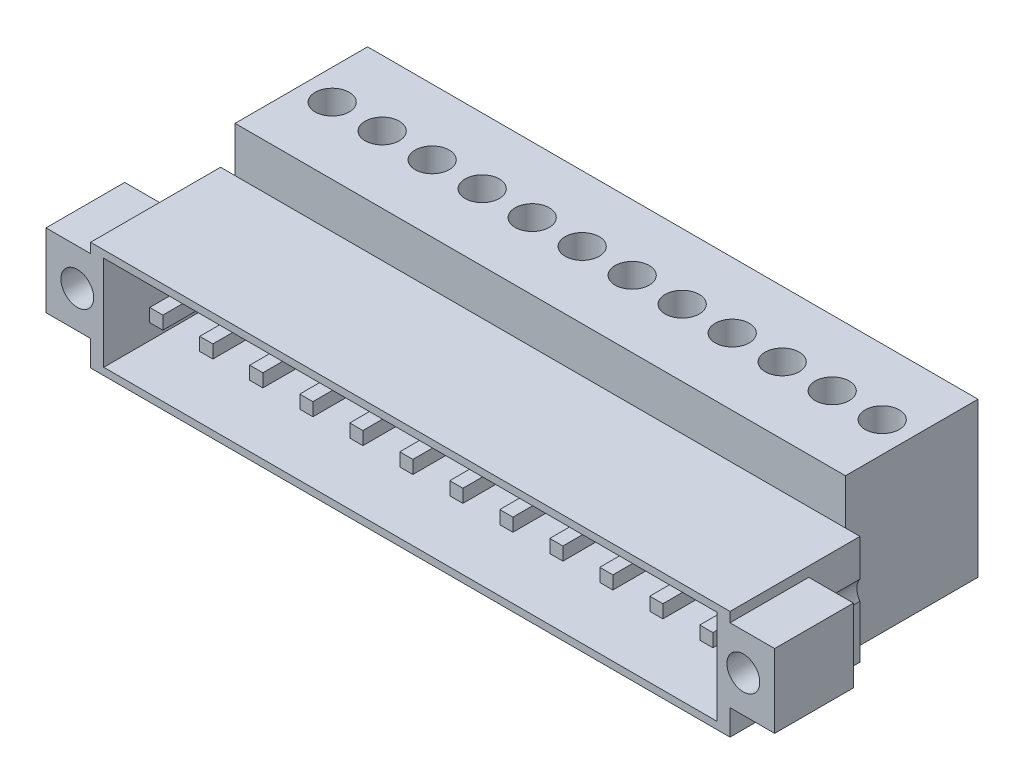
SolidWorks part; units mm, degrees
ref_plane "Front Plane" through (0, 0, 0) normal (0, 0, 1) x (1, 0, 0)
ref_plane "Top Plane" through (0, 0, 0) normal (0, 1, 0) x (1, 0, 0)
ref_plane "Right Plane" through (0, 0, 0) normal (1, 0, 0) x (0, 0, -1)
ref_plane "PL mating face" through (0, 0, 3) normal (0, 0, 1) x (1, 0, 0)
sketch "SK Shroud" plane through (0, 0, 3) normal (0, 0, 1) x (1, 0, 0)
  line L0 (-24.36, -4.75) -> (24.36, -4.75)
  line L1 (24.36, -4.75) -> (24.36, 3.55)
  line L2 (24.36, 3.55) -> (-24.36, 3.55)
  line L3 (-24.36, 3.55) -> (-24.36, -4.75)
extrude "Shroud" add sketch "SK Shroud" against normal blind 9.9
sketch "SK Flange ears" plane through (0, 0, 3) normal (0, 0, 1) x (1, 0, 0)
  line L0 (24.36, -2.8) -> (27.76, -2.8)
  line L1 (27.76, -2.8) -> (27.76, 2.8)
  line L2 (27.76, 2.8) -> (24.36, 2.8)
  line L3 (24.36, 2.8) -> (24.36, -2.8)
  line L4 (-27.76, -2.8) -> (-24.36, -2.8)
  line L5 (-24.36, -2.8) -> (-24.36, 2.8)
  line L6 (-24.36, 2.8) -> (-27.76, 2.8)
  line L7 (-27.76, 2.8) -> (-27.76, -2.8)
extrude "Flange ears" add sketch "SK Flange ears" against normal blind 6
sketch "SK Cavity" plane through (0, 0, 3) normal (0, 0, 1) x (1, 0, 0)
  line L0 (-23.36, -4.2) -> (23.36, -4.2)
  line L1 (23.36, -4.2) -> (23.36, 3)
  line L2 (23.36, 3) -> (-23.36, 3)
  line L3 (-23.36, 3) -> (-23.36, -4.2)
extrude "Cavity" cut sketch "SK Cavity" against normal blind 7.6
ref_plane "PL shroud rear" through (0, 0, -6.9) normal (0, 0, 1) x (1, 0, 0)
sketch "SK Terminal block" plane through (0, 0, -6.9) normal (0, 0, 1) x (1, 0, 0)
  line L0 (-23.255, -4.75) -> (23.255, -4.75)
  line L1 (23.255, -4.75) -> (23.255, 7)
  line L2 (23.255, 7) -> (-23.255, 7)
  line L3 (-23.255, 7) -> (-23.255, -4.75)
extrude "Terminal block" add sketch "SK Terminal block" against normal blind 10.1
sketch "SK Insert holes" plane through (0, 0, 0) normal (0, 0, 1) x (1, 0, 0)
  circle A0 centre (-25.375, 0) radius 1.25
  circle A1 centre (25.375, 0) radius 1.25
extrude "Insert holes" cut sketch "SK Insert holes" against normal through all and the other way through all
ref_plane "PL cavity floor" through (0, 0, -4.6) normal (0, 0, 1) x (1, 0, 0)
sketch "SK Contact pins" plane through (0, 0, -4.6) normal (0, 0, 1) x (1, 0, 0)
  line L0 (-21.455, -1.1) -> (-20.455, -1.1)
  line L1 (-20.455, -1.1) -> (-20.455, -0.1)
  line L2 (-20.455, -0.1) -> (-21.455, -0.1)
  line L3 (-21.455, -0.1) -> (-21.455, -1.1)
  line L4 (-17.645, -1.1) -> (-16.645, -1.1)
  line L5 (-16.645, -1.1) -> (-16.645, -0.1)
  line L6 (-16.645, -0.1) -> (-17.645, -0.1)
  line L7 (-17.645, -0.1) -> (-17.645, -1.1)
  line L8 (-13.835, -1.1) -> (-12.835, -1.1)
  line L9 (-12.835, -1.1) -> (-12.835, -0.1)
  line L10 (-12.835, -0.1) -> (-13.835, -0.1)
  line L11 (-13.835, -0.1) -> (-13.835, -1.1)
  line L12 (-10.025, -1.1) -> (-9.025, -1.1)
  line L13 (-9.025, -1.1) -> (-9.025, -0.1)
  line L14 (-9.025, -0.1) -> (-10.025, -0.1)
  line L15 (-10.025, -0.1) -> (-10.025, -1.1)
  line L16 (-6.215, -1.1) -> (-5.215, -1.1)
  line L17 (-5.215, -1.1) -> (-5.215, -0.1)
  line L18 (-5.215, -0.1) -> (-6.215, -0.1)
  line L19 (-6.215, -0.1) -> (-6.215, -1.1)
  line L20 (-2.405, -1.1) -> (-1.405, -1.1)
  line L21 (-1.405, -1.1) -> (-1.405, -0.1)
  line L22 (-1.405, -0.1) -> (-2.405, -0.1)
  line L23 (-2.405, -0.1) -> (-2.405, -1.1)
  line L24 (1.405, -1.1) -> (2.405, -1.1)
  line L25 (2.405, -1.1) -> (2.405, -0.1)
  line L26 (2.405, -0.1) -> (1.405, -0.1)
  line L27 (1.405, -0.1) -> (1.405, -1.1)
  line L28 (5.215, -1.1) -> (6.215, -1.1)
  line L29 (6.215, -1.1) -> (6.215, -0.1)
  line L30 (6.215, -0.1) -> (5.215, -0.1)
  line L31 (5.215, -0.1) -> (5.215, -1.1)
  line L32 (9.025, -1.1) -> (10.025, -1.1)
  line L33 (10.025, -1.1) -> (10.025, -0.1)
  line L34 (10.025, -0.1) -> (9.025, -0.1)
  line L35 (9.025, -0.1) -> (9.025, -1.1)
  line L36 (12.835, -1.1) -> (13.835, -1.1)
  line L37 (13.835, -1.1) -> (13.835, -0.1)
  line L38 (13.835, -0.1) -> (12.835, -0.1)
  line L39 (12.835, -0.1) -> (12.835, -1.1)
  line L40 (16.645, -1.1) -> (17.645, -1.1)
  line L41 (17.645, -1.1) -> (17.645, -0.1)
  line L42 (17.645, -0.1) -> (16.645, -0.1)
  line L43 (16.645, -0.1) -> (16.645, -1.1)
  line L44 (20.455, -1.1) -> (21.455, -1.1)
  line L45 (21.455, -1.1) -> (21.455, -0.1)
  line L46 (21.455, -0.1) -> (20.455, -0.1)
  line L47 (20.455, -0.1) -> (20.455, -1.1)
extrude "Contact pins" add sketch "SK Contact pins" along normal blind 6
ref_plane "PL wire face" through (0, 0, -17) normal (0, 0, 1) x (1, 0, 0)
sketch "SK Wire entries" plane through (0, 0, -17) normal (0, 0, 1) x (1, 0, 0)
  line L0 (-22.255, -3.4) -> (-19.655, -3.4)
  line L1 (-19.655, -3.4) -> (-19.655, -0.6)
  line L2 (-19.655, -0.6) -> (-22.255, -0.6)
  line L3 (-22.255, -0.6) -> (-22.255, -3.4)
  line L4 (-18.445, -3.4) -> (-15.845, -3.4)
  line L5 (-15.845, -3.4) -> (-15.845, -0.6)
  line L6 (-15.845, -0.6) -> (-18.445, -0.6)
  line L7 (-18.445, -0.6) -> (-18.445, -3.4)
  line L8 (-14.635, -3.4) -> (-12.035, -3.4)
  line L9 (-12.035, -3.4) -> (-12.035, -0.6)
  line L10 (-12.035, -0.6) -> (-14.635, -0.6)
  line L11 (-14.635, -0.6) -> (-14.635, -3.4)
  line L12 (-10.825, -3.4) -> (-8.225, -3.4)
  line L13 (-8.225, -3.4) -> (-8.225, -0.6)
  line L14 (-8.225, -0.6) -> (-10.825, -0.6)
  line L15 (-10.825, -0.6) -> (-10.825, -3.4)
  line L16 (-7.015, -3.4) -> (-4.415, -3.4)
  line L17 (-4.415, -3.4) -> (-4.415, -0.6)
  line L18 (-4.415, -0.6) -> (-7.015, -0.6)
  line L19 (-7.015, -0.6) -> (-7.015, -3.4)
  line L20 (-3.205, -3.4) -> (-0.605, -3.4)
  line L21 (-0.605, -3.4) -> (-0.605, -0.6)
  line L22 (-0.605, -0.6) -> (-3.205, -0.6)
  line L23 (-3.205, -0.6) -> (-3.205, -3.4)
  line L24 (0.605, -3.4) -> (3.205, -3.4)
  line L25 (3.205, -3.4) -> (3.205, -0.6)
  line L26 (3.205, -0.6) -> (0.605, -0.6)
  line L27 (0.605, -0.6) -> (0.605, -3.4)
  line L28 (4.415, -3.4) -> (7.015, -3.4)
  line L29 (7.015, -3.4) -> (7.015, -0.6)
  line L30 (7.015, -0.6) -> (4.415, -0.6)
  line L31 (4.415, -0.6) -> (4.415, -3.4)
  line L32 (8.225, -3.4) -> (10.825, -3.4)
  line L33 (10.825, -3.4) -> (10.825, -0.6)
  line L34 (10.825, -0.6) -> (8.225, -0.6)
  line L35 (8.225, -0.6) -> (8.225, -3.4)
  line L36 (12.035, -3.4) -> (14.635, -3.4)
  line L37 (14.635, -3.4) -> (14.635, -0.6)
  line L38 (14.635, -0.6) -> (12.035, -0.6)
  line L39 (12.035, -0.6) -> (12.035, -3.4)
  line L40 (15.845, -3.4) -> (18.445, -3.4)
  line L41 (18.445, -3.4) -> (18.445, -0.6)
  line L42 (18.445, -0.6) -> (15.845, -0.6)
  line L43 (15.845, -0.6) -> (15.845, -3.4)
  line L44 (19.655, -3.4) -> (22.255, -3.4)
  line L45 (22.255, -3.4) -> (22.255, -0.6)
  line L46 (22.255, -0.6) -> (19.655, -0.6)
  line L47 (19.655, -0.6) -> (19.655, -3.4)
extrude "Wire entries" cut sketch "SK Wire entries" along normal blind 6
ref_plane "PL top face" through (0, 7, 0) normal (0, 1, 0) x (1, 0, 0)
sketch "SK Clamp screw holes" plane through (0, 7, 0) normal (0, 1, 0) x (1, 0, 0)
  circle A0 centre (-20.955, 12) radius 1.3
  circle A1 centre (-17.145, 12) radius 1.3
  circle A2 centre (-13.335, 12) radius 1.3
  circle A3 centre (-9.525, 12) radius 1.3
  circle A4 centre (-5.715, 12) radius 1.3
  circle A5 centre (-1.905, 12) radius 1.3
  circle A6 centre (1.905, 12) radius 1.3
  circle A7 centre (5.715, 12) radius 1.3
  circle A8 centre (9.525, 12) radius 1.3
  circle A9 centre (13.335, 12) radius 1.3
  circle A10 centre (17.145, 12) radius 1.3
  circle A11 centre (20.955, 12) radius 1.3
extrude "Clamp screw holes" cut sketch "SK Clamp screw holes" against normal blind 3
